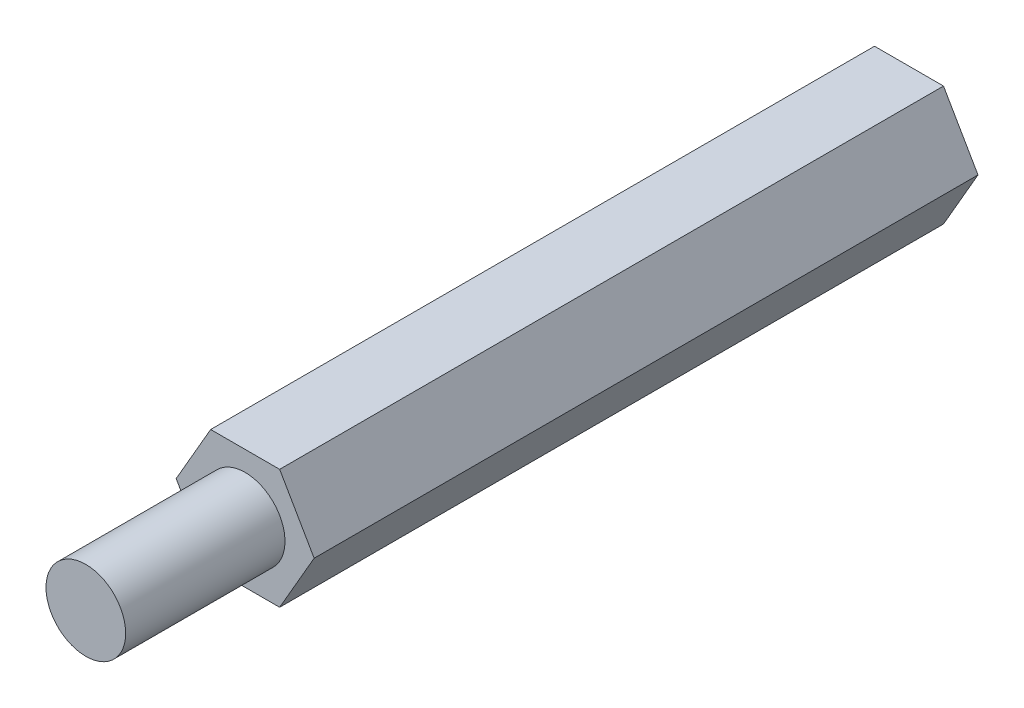
SolidWorks part; units mm, degrees
material "Aluminum"
ref_plane "Front Plane" through (0, 0, 0) normal (0, 0, 1) x (1, 0, 0)
ref_plane "Top Plane" through (0, 0, 0) normal (0, 1, 0) x (1, 0, 0)
ref_plane "Right Plane" through (0, 0, 0) normal (1, 0, 0) x (0, 0, -1)
sketch "Sketch1" plane through (0, 0, 0) normal (0, 0, 1) x (1, 0, 0)
  circle A0 centre (0, 0) radius 1.5
  dimension "D1" = 3
extrude "Boss-Extrude1" add sketch "Sketch1" along normal blind 6
sketch "Sketch2" plane through (0, 0, 0) normal (0, 0, -1) x (-1, 0, 0)
  line L1 (-1.299, 2.25) -> (-2.5981, 0)
  line L2 (-2.5981, 0) -> (-1.299, -2.25)
  line L3 (-1.299, -2.25) -> (1.299, -2.25)
  line L4 (1.299, -2.25) -> (2.5981, 0)
  line L5 (2.5981, 0) -> (1.299, 2.25)
  line L6 (1.299, 2.25) -> (-1.299, 2.25)
  circle A1 centre (0, 0) radius 2.25 construction
  dimension "D2" = 4.5
extrude "Boss-Extrude2" add sketch "Sketch2" along normal blind 25
sketch "Sketch3" plane through (0, 0, -25) normal (0, 0, -1) x (-1, 0, 0)
  circle A0 centre (0, 0) radius 1.5
  dimension "D1" = 3
extrude "Cut-Extrude1" cut sketch "Sketch3" against normal blind 4.5
